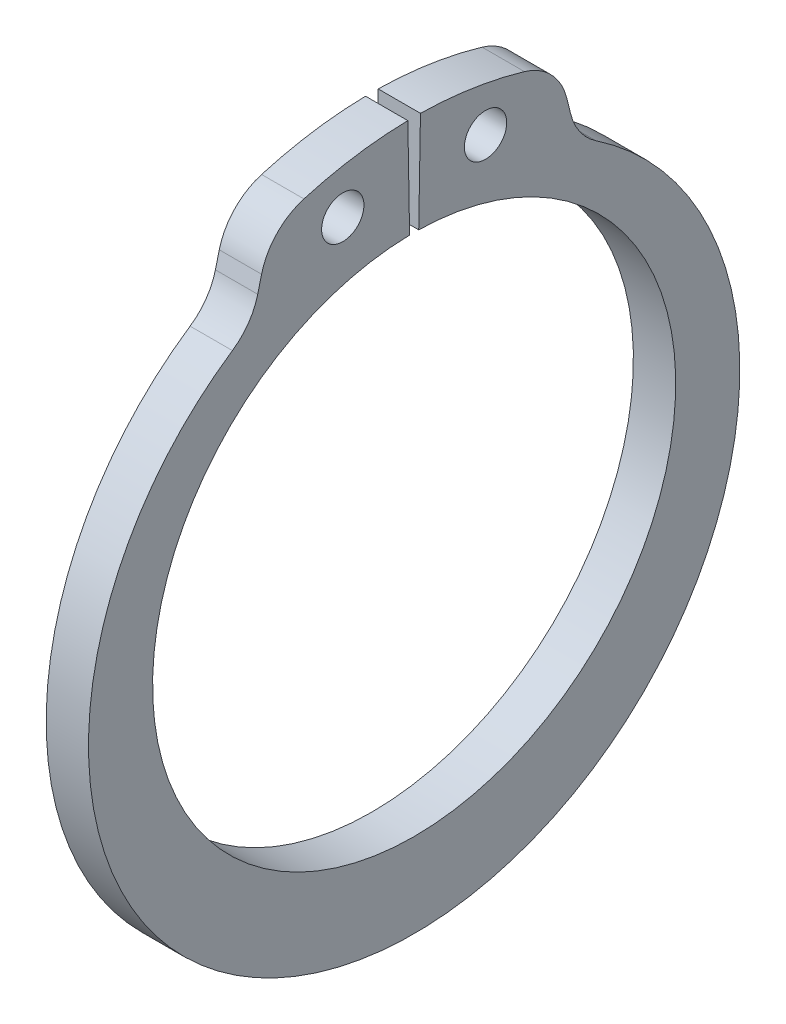
SolidWorks part; units mm, degrees
material "Cast Carbon Steel"
ref_plane "Front" through (0, 0, 0) normal (0, 0, 1) x (1, 0, 0)
ref_plane "Top" through (0, 0, 0) normal (0, 1, 0) x (1, 0, 0)
ref_plane "Right" through (0, 0, 0) normal (1, 0, 0) x (0, 0, -1)
sketch "Sketch1" plane through (0, 0, 0) normal (1, 0, 0) x (0, 0, -1)
  line L0 (0, 0) -> (0, 14.605) construction
  line L1 (-0.2549, 14.6028) -> (-0.3524, 20.1899)
  line L2 (-0.3524, 20.1899) -> (-7.7178, 20.0614) construction
  line L3 (-7.7178, 20.0614) -> (-9.0697, 14.6393) construction
  line L4 (0.3524, 20.1899) -> (0.2549, 14.6028)
  line L5 (0.3524, 20.1899) -> (7.7178, 20.0614) construction
  line L6 (7.7178, 20.0614) -> (9.0697, 14.6393) construction
  line L7 (-9.0697, 14.6393) -> (-7.6918, 12.4154) construction
  line L8 (9.0697, 14.6393) -> (7.6918, 12.4154) construction
  line L9 (0, -14.605) -> (0, -19.304) construction
  line L10 (-7.7178, 20.0614) -> (-0.2549, 14.6028) construction
  line L11 (-14.605, 0) -> (14.605, 0) construction
  line L12 (0, 14.605) -> (0, 20.193) construction
  line L13 (8.07, 18.6488) -> (9.0697, 14.6393)
  line L14 (-8.07, 18.6488) -> (-9.0697, 14.6393)
  circle A0 centre (0, 0) radius 14.605 construction
  arc A1 (-0.2549, 14.6028) -> (0.2549, 14.6028) centre (0, 0) ccw
  circle A2 centre (0, -1.1206) radius 18.1834 construction
  circle A3 centre (0, 0) radius 20.32 construction
  circle A4 centre (-3.9864, 17.3321) radius 1.1811
  circle A5 centre (3.9864, 17.3321) radius 1.1811
  arc A6 (-9.0697, 14.6393) -> (9.0697, 14.6393) centre (0, -1.1206) ccw
  arc A7 (0.3524, 20.1899) -> (8.07, 18.6488) centre (-0.0319, -1.8292) cw
  arc A8 (-0.3524, 20.1899) -> (-8.07, 18.6488) centre (0.0319, -1.8292) ccw
  dimension "D1" = 75
  dimension "A" = 29.21
  dimension "L" = 40.64
  dimension "Hole" = 2.3622
  dimension "Smin" = 2.6162
  dimension "Smax" = 4.699
  dimension "H" = 5.588
  dimension "Angle" = 1
extrude "Extrude1" add sketch "Sketch1" along normal mid plane 2.3622
fillet "Fillet1" radius 3.429 4 edges at (0, 14.6393, 9.0697) (0, 18.6488, 8.07) (0, 18.6488, -8.07) (0, 14.6393, -9.0697)
sketch "Sketch2" plane through (0, 0, 0) normal (0, 0, 1) x (1, 0, 0)
  line L0 (-6.5405, 0) -> (19.6215, 0)
  line L1 (19.6215, 0) -> (19.6215, -15.875)
  line L3 (19.6215, -15.875) -> (1.3081, -15.875)
  line L4 (1.3081, -15.875) -> (1.3081, -14.9098)
  line L5 (1.3081, -14.9098) -> (-1.3081, -14.9098)
  line L6 (-1.3081, -14.9098) -> (-1.3081, -15.875)
  line L7 (-1.3081, -15.875) -> (-6.5405, -15.875) construction
  line L8 (-6.5405, -15.875) -> (-6.5405, 0) construction
  line L9 (0, -14.9098) -> (0, 0) construction
  line L10 (19.6215, 0) -> (14.0551, 0) construction
  line L11 (-1.3081, -15.875) -> (-6.0579, -15.875)
  line L12 (-6.0579, -15.875) -> (-6.5405, -15.3924)
  line L13 (-6.5405, -15.3924) -> (-6.5405, 0)
  point P14 (-1.3081, -15.3924)
  dimension "Dg" = 29.8196
  dimension "Ds" = 31.75
  dimension "D2" = 26.162
  dimension "W" = 2.6162
  dimension "D3" = 6.5405
  dimension "D4" = 45
revolve "Revolve1" [suppressed] add sketch "Sketch2" angle 360 about L10
equation "\"D2@Sketch2\" = \"W@Sketch2\"*10"
equation "\"D3@Sketch2\" = \"D2@Sketch2\"/4"
